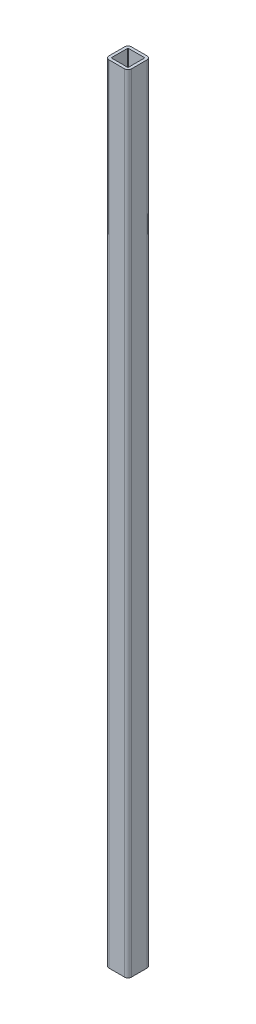
SolidWorks part; units mm, degrees
material "AISI 1015 Steel, Cold Drawn (SS)"
ref_plane "Front Plane" through (0, 0, 0) normal (0, 0, 1) x (1, 0, 0)
ref_plane "Top Plane" through (0, 0, 0) normal (0, 1, 0) x (1, 0, 0)
ref_plane "Right Plane" through (0, 0, 0) normal (1, 0, 0) x (0, 0, -1)
sketch "Sketch2" plane through (0, 0, 0) normal (0, 1, 0) x (1, 0, 0)
  line L0 (-17.78, -19.05) -> (17.78, -19.05)
  line L1 (-17.78, -25.4) -> (17.78, -25.4)
  line L2 (-25.4, -17.78) -> (-25.4, 17.78)
  line L3 (-17.78, 25.4) -> (17.78, 25.4)
  line L4 (25.4, -17.78) -> (25.4, 17.78)
  line L5 (-25.4, -25.4) -> (25.4, 25.4) construction
  line L6 (-25.4, 25.4) -> (25.4, -25.4) construction
  line L7 (19.05, -17.78) -> (19.05, 17.78)
  line L8 (-17.78, 19.05) -> (17.78, 19.05)
  line L9 (-19.05, -17.78) -> (-19.05, 17.78)
  arc A0 (17.78, 25.4) -> (25.4, 17.78) centre (17.78, 17.78) cw
  arc A1 (17.78, -25.4) -> (25.4, -17.78) centre (17.78, -17.78) ccw
  arc A2 (-17.78, -25.4) -> (-25.4, -17.78) centre (-17.78, -17.78) cw
  arc A3 (-25.4, 17.78) -> (-17.78, 25.4) centre (-17.78, 17.78) cw
  arc A4 (17.78, -19.05) -> (19.05, -17.78) centre (17.78, -17.78) ccw
  arc A5 (17.78, 19.05) -> (19.05, 17.78) centre (17.78, 17.78) cw
  arc A6 (-19.05, 17.78) -> (-17.78, 19.05) centre (-17.78, 17.78) cw
  arc A7 (-17.78, -19.05) -> (-19.05, -17.78) centre (-17.78, -17.78) cw
  point P0 (0, 0)
  point P6 (0, 0)
  dimension "D3" = 1.27
  dimension "D1" = 50.8
  dimension "D2" = 50.8
  dimension "D4" = 6.35
extrude "Boss-Extrude1" add sketch "Sketch2" along normal blind 1778
equation "\"D4@Sketch2\"=\"Wall Thickness\""
equation "\"D1@Boss-Extrude1\"=\"Length\""
